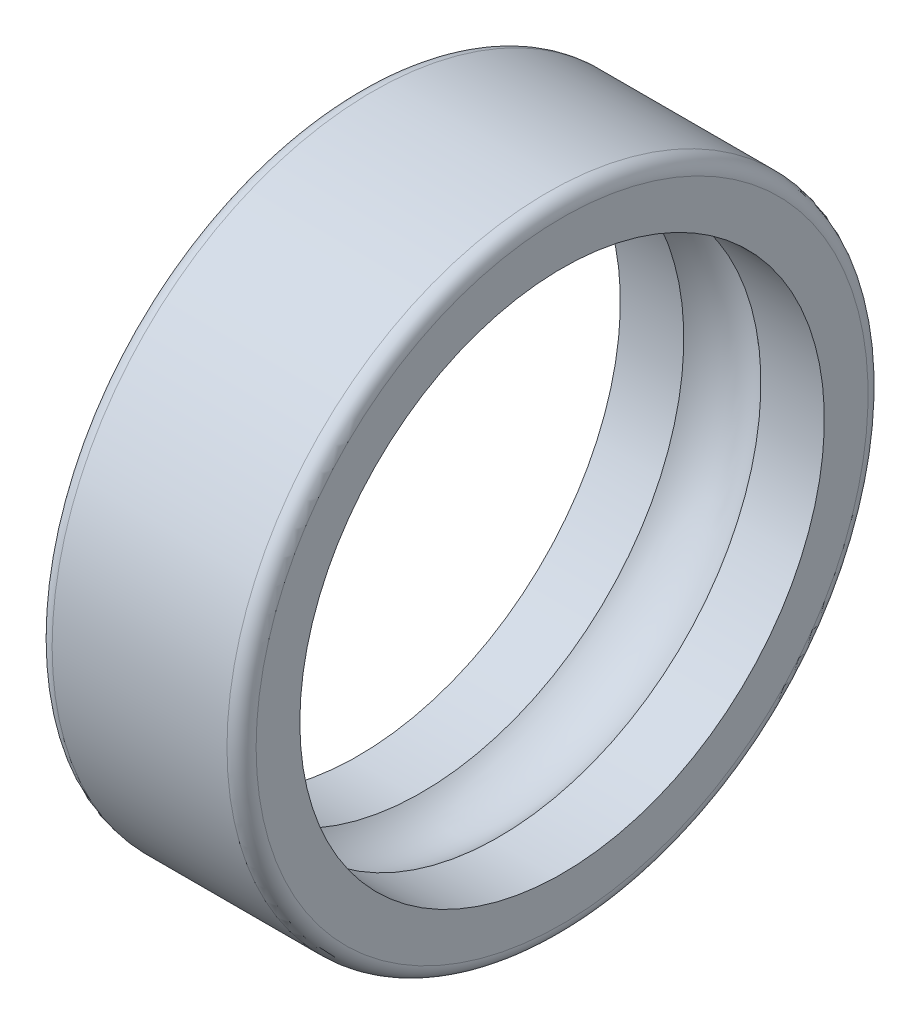
SolidWorks part; units mm, degrees
ref_plane "Plan1" through (0, 0, 0) normal (0, 0, 1) x (1, 0, 0)
ref_plane "Plan2" through (0, 0, 0) normal (0, 1, 0) x (1, 0, 0)
ref_plane "Plan3" through (0, 0, 0) normal (1, 0, 0) x (0, 0, -1)
sketch "Esquisse1" plane through (0, 0, 0) normal (0, 0, 1) x (1, 0, 0)
  line L0 (-3.5, 4) -> (-3.5, 11) construction
  line L1 (-3, 11) -> (3, 11)
  line L2 (-3.5, 10.5) -> (-3.5, 9)
  line L3 (-3.5, 9) -> (-1.3229, 9)
  line L4 (3.5, 10.5) -> (3.5, 9)
  line L5 (3.5, 4) -> (3.5, 11) construction
  line L6 (-3.5, 11) -> (3.5, 11) construction
  line L7 (1.3229, 9) -> (3.5, 9)
  line L8 (0, 0) -> (15, 0) construction
  line L9 (0, 0) -> (54, 0) construction
  arc A0 (3, 11) -> (3.5, 10.5) centre (3, 10.5) cw
  arc A1 (-3, 11) -> (-3.5, 10.5) centre (-3, 10.5) ccw
  arc A2 (1.3229, 9) -> (-1.3229, 9) centre (0, 7.5) ccw
  point P12 (3.5, 11)
  dimension "D2" = 0.5
  dimension "D3" = 2
  dimension "D1" = 2
revolve "Base-Révolution" add sketch "Esquisse1" angle 360 about L8
